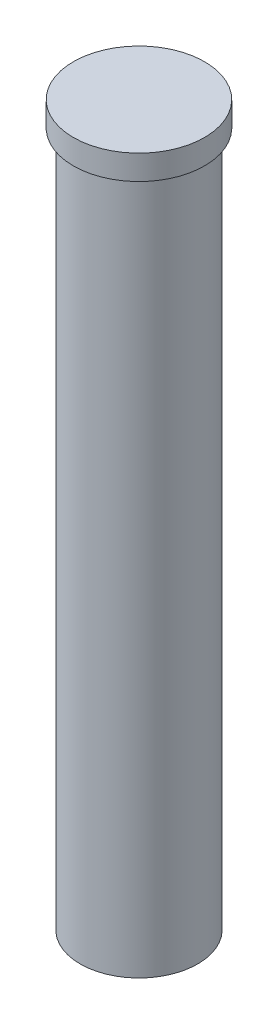
SolidWorks part; units mm, degrees
ref_plane "Front Plane" through (0, 0, 0) normal (0, 0, 1) x (1, 0, 0)
ref_plane "Top Plane" through (0, 0, 0) normal (0, 1, 0) x (1, 0, 0)
ref_plane "Right Plane" through (0, 0, 0) normal (1, 0, 0) x (0, 0, -1)
sketch "Sketch1" plane through (0, 0, 0) normal (0, 1, 0) x (1, 0, 0)
  circle A0 centre (0, 0) radius 2.15
  dimension "D1" = 4.3
extrude "Boss-Extrude1" add sketch "Sketch1" along normal blind 26.3
sketch "Sketch2" plane through (0, 26.3, 0) normal (0, 1, 0) x (1, 0, 0)
  circle A0 centre (0, 0) radius 2.4
  dimension "D1" = 4.8
extrude "Boss-Extrude2" add sketch "Sketch2" against normal blind 0.9
